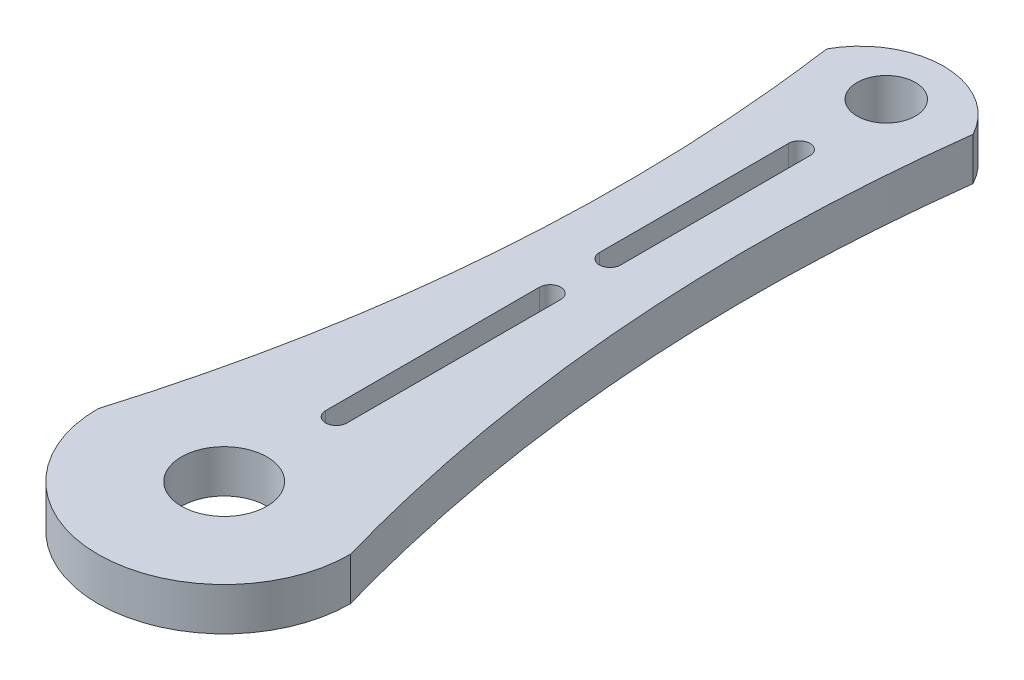
SolidWorks part; units mm, degrees
material "PF"
ref_plane "前视基准面" through (0, 0, 0) normal (0, 0, 1) x (1, 0, 0)
ref_plane "上视基准面" through (0, 0, 0) normal (0, 1, 0) x (1, 0, 0)
ref_plane "右视基准面" through (0, 0, 0) normal (1, 0, 0) x (0, 0, -1)
sketch "草图1" plane through (0, 0, 0) normal (0, 1, 0) x (1, 0, 0)
  line L6 (-19.5, 150) -> (-29.5, 0)
  line L7 (19.4734, 150.0034) -> (29.5, 0)
  arc A1 (-29.5, 0) -> (29.5, 0) centre (0, 0) ccw
  arc A2 (-19.5, 150) -> (19.4734, 150.0034) centre (-0.0132, 148.7009) cw
  dimension "D1" = 29.5
  dimension "D2" = 150
extrude "凸台-拉伸1" add sketch "草图1" along normal blind 10
sketch "草图2" plane through (0, 10, 0) normal (0, 1, 0) x (1, 0, 0)
  line L5 (-19.5, 150) -> (-29.5, 0) construction
  line L6 (29.5, 0) -> (19.4734, 150.0034) construction
  line L7 (-18.4065, 166.4025) -> (-29.5, 0)
  line L8 (18.3774, 166.4003) -> (29.5, 0)
  arc A1 (-29.5, 0) -> (29.5, 0) centre (0, 0) ccw construction
  spline S0 degree 2 poles (-18.4065, 166.4025) (-4.8876, 82.1234) (-29.5, 0) knots 0 0 0 1 1 1
  spline S1 degree 2 poles (18.3774, 166.4003) (6.1003, 82.1763) (29.5, 0) knots 0 0 0 1 1 1
extrude "切除-拉伸1" cut sketch "草图2" against normal through all
sketch "草图3" plane through (0, 10, 0) normal (0, 1, 0) x (1, 0, 0)
  line L0 (0, 90.2154) -> (0, 134.4749) construction
  line L1 (-2.5, 90.2154) -> (-2.5, 134.4749)
  line L2 (2.5, 90.2154) -> (2.5, 134.4749)
  line L3 (0, 76.2052) -> (0, 26.2144) construction
  line L4 (2.5, 76.2052) -> (2.5, 26.2144)
  line L5 (-2.5, 76.2052) -> (-2.5, 26.2144)
  arc A0 (-2.5, 90.2154) -> (2.5, 90.2154) centre (0, 90.2154) ccw
  arc A1 (2.5, 134.4749) -> (-2.5, 134.4749) centre (0, 134.4749) ccw
  arc A2 (2.5, 76.2052) -> (-2.5, 76.2052) centre (0, 76.2052) ccw
  arc A3 (-2.5, 26.2144) -> (2.5, 26.2144) centre (0, 26.2144) ccw
  point P3 (0, 112.3451)
  point P8 (0, 51.2098)
  dimension "D1" = 5
  dimension "D2" = 5
extrude "切除-拉伸2" cut sketch "草图3" against normal through all
sketch "草图4" plane through (0, 10, 0) normal (0, 1, 0) x (1, 0, 0)
  circle A0 centre (0, 154.8091) radius 6.8229
extrude "切除-拉伸3" cut sketch "草图4" against normal through all
sketch "草图5" plane through (0, 10, 0) normal (0, 1, 0) x (1, 0, 0)
  circle A0 centre (0, 0) radius 10
  dimension "D1" = 20
extrude "切除-拉伸4" cut sketch "草图5" against normal through all
